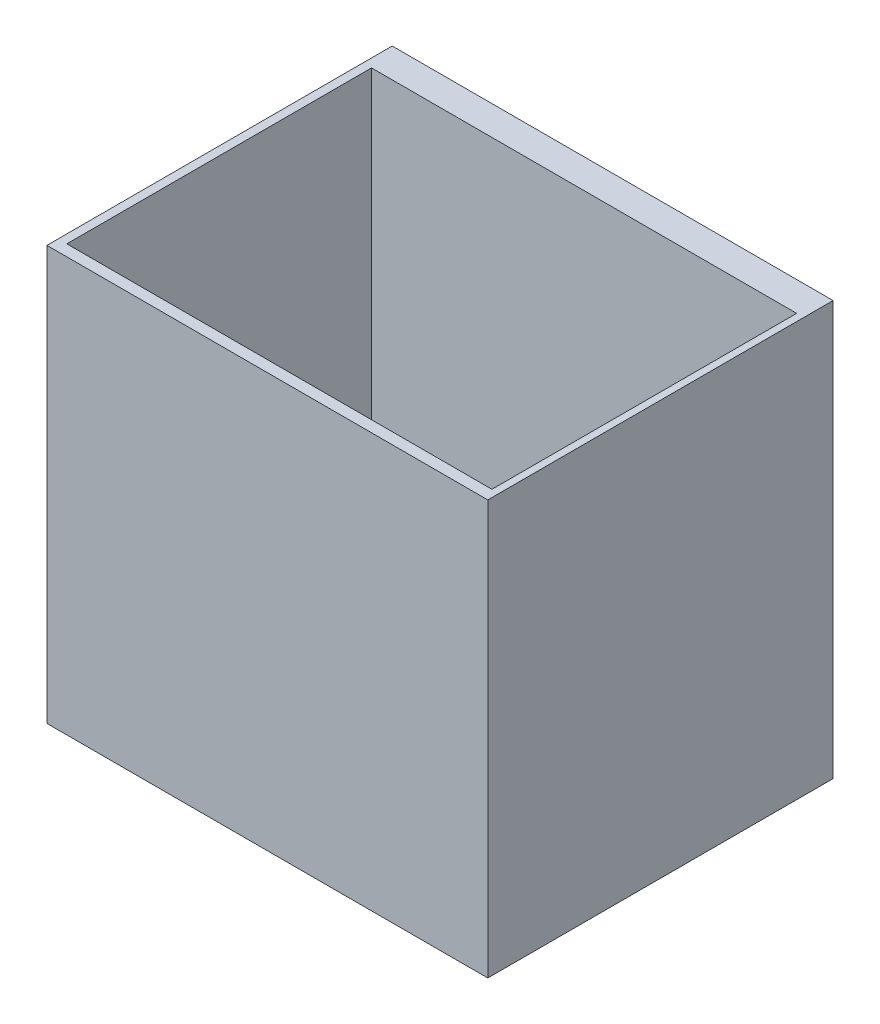
SolidWorks part; units mm, degrees
ref_plane "Front Plane" through (0, 0, 0) normal (0, 0, 1) x (1, 0, 0)
ref_plane "Top Plane" through (0, 0, 0) normal (0, 1, 0) x (1, 0, 0)
ref_plane "Right Plane" through (0, 0, 0) normal (1, 0, 0) x (0, 0, -1)
sketch "Sketch2" plane through (0, 0, 943.5108) normal (0, 0, 1) x (1, 0, 0)
  line L1 (518.1595, 769) -> (1134.8675, 769)
  line L2 (518.1595, 769) -> (518.1595, 189.835)
  line L3 (518.1595, 189.835) -> (1134.8675, 189.835)
  line L4 (1134.8675, 769) -> (1134.8675, 189.835)
extrude "Boss-Extrude1" add sketch "Sketch2" along normal blind 483 from offset 710
sketch "Sketch3" plane through (0, 769, 0) normal (0, 1, 0) x (1, 0, 0)
  line L1 (1124.9032, -2120.7422) -> (530.2309, -2120.7422)
  line L2 (1124.9032, -2120.7422) -> (1124.9032, -1694.5139)
  line L3 (1124.9032, -1694.5139) -> (530.2309, -1694.5139)
  line L4 (530.2309, -2120.7422) -> (530.2309, -1694.5139)
extrude "Cut-Extrude1" cut sketch "Sketch3" against normal blind 568
sketch "Sketch4" plane through (0, 769, 0) normal (0, 1, 0) x (1, 0, 0)
  line L0 (1134.8675, -1653.5108) -> (518.1595, -1653.5108) construction
  line L1 (882.6171, -1653.6882) -> (882.6171, -1607.727) construction
  line L2 (826.5135, -1680.1274) -> (826.5135, -1653.5108)
  line L3 (882.6171, -1653.5108) -> (826.5135, -1653.5108)
  arc A0 (882.6171, -1653.5108) -> (826.5135, -1680.1274) centre (834.5393, -1624.6074) cw
extrude "Cut-Extrude2" cut sketch "Sketch4" against normal blind 23 from offset 100
